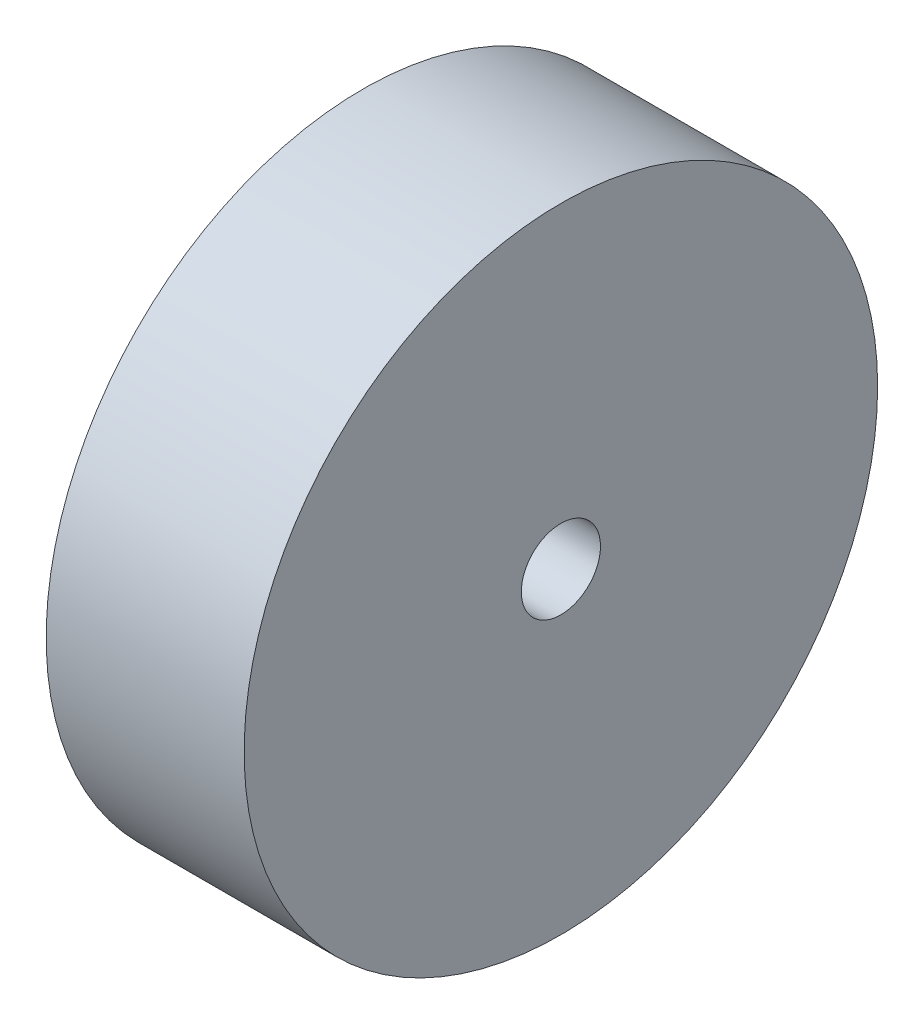
SolidWorks part; units mm, degrees
material "6063-O"
ref_plane "Plano frontal" through (0, 0, 0) normal (0, 0, 1) x (1, 0, 0)
ref_plane "Plano superior" through (0, 0, 0) normal (0, 1, 0) x (1, 0, 0)
ref_plane "Plano direito" through (0, 0, 0) normal (1, 0, 0) x (0, 0, -1)
sketch "Esboço3" plane through (0, 0, 0) normal (0, 0, 1) x (1, 0, 0)
  line L0 (0, 0) -> (-50.7324, 0) construction
  line L1 (0, 16) -> (0, 2)
  line L2 (-2, 10) -> (-2, 5)
  line L3 (-10, 5) -> (-10, 0)
  line L4 (-2, 5) -> (-10, 5)
  line L5 (-10, 0) -> (-8, 0)
  line L6 (-8, 2) -> (0, 2)
  line L7 (-2, 10) -> (-10, 10)
  line L8 (-10, 10) -> (-10, 16)
  line L9 (-10, 16) -> (0, 16)
  line L10 (-8, 0) -> (-8, 2)
  dimension "D1" = 2
  dimension "D2" = 16
  dimension "D3" = 6
  dimension "D4" = 10
  dimension "D5" = 5
  dimension "D6" = 2
  dimension "D7" = 10
  dimension "D8" = 2
revolve "Revolução1" add sketch "Esboço3" angle 360 about L0
ref_plane "Plano1" through (0, 5, 0) normal (0, 1, 0) x (1, 0, 0)
sketch "Esboço6" plane through (0, 5, 0) normal (0, 1, 0) x (1, 0, 0)
  line L0 (-10, 16) -> (-10, -16) construction
  circle A0 centre (-5, 0) radius 0.8
  dimension "D1" = 1.6
  dimension "D2" = 5
extrude "Corte-extrusão1" [suppressed] cut sketch "Esboço6" against normal mid plane 70
equation "\"D4@Esboço3\"=\"D7@Esboço3\""
